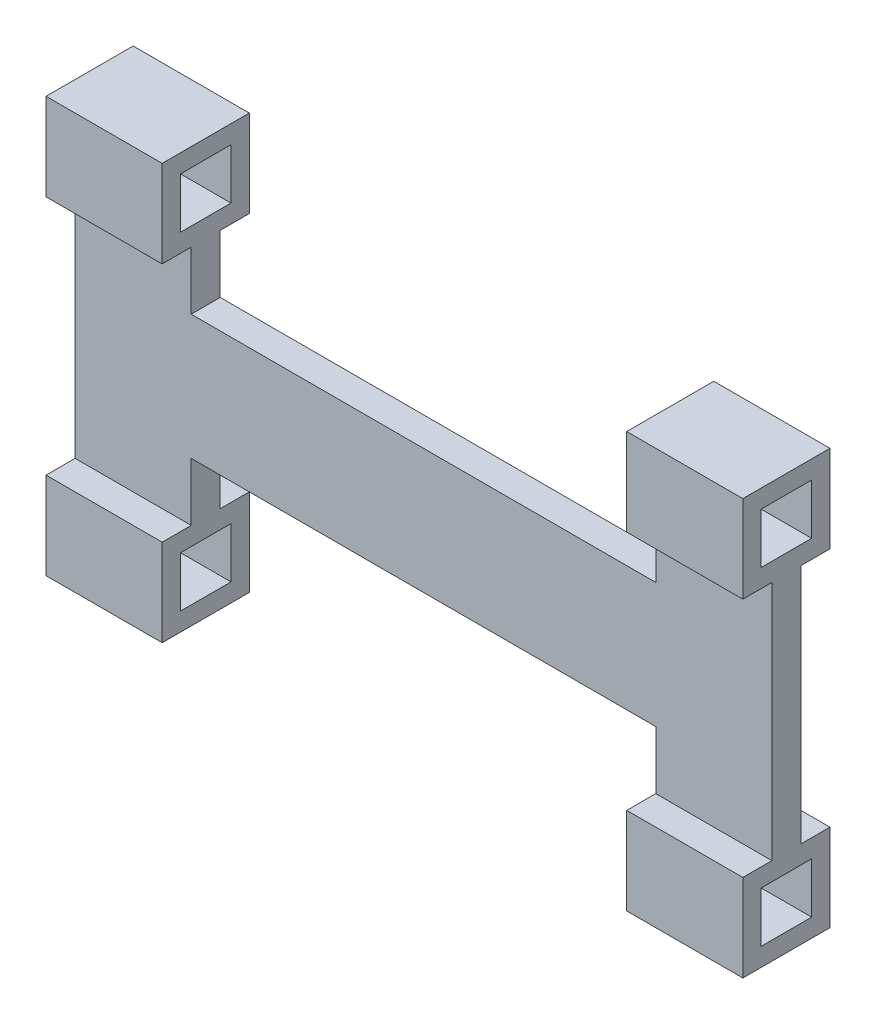
SolidWorks part; units mm, degrees
ref_plane "前视基准面" through (0, 0, 0) normal (0, 0, 1) x (1, 0, 0)
ref_plane "上视基准面" through (0, 0, 0) normal (0, 1, 0) x (1, 0, 0)
ref_plane "右视基准面" through (0, 0, 0) normal (1, 0, 0) x (0, 0, -1)
sketch "草图1" plane through (0, 0, 0) normal (1, 0, 0) x (0, 0, -1)
  line L0 (0, 0) -> (0, 11.3) construction
  line L1 (-0.87, -0.87) -> (0.87, -0.87)
  line L2 (-0.87, -0.87) -> (-0.87, 0.87)
  line L3 (-0.87, 0.87) -> (0.87, 0.87)
  line L4 (0.87, -0.87) -> (0.87, 0.87)
  line L5 (-0.87, -0.87) -> (0.87, 0.87) construction
  line L6 (-0.87, 0.87) -> (0.87, -0.87) construction
  line L7 (-0.87, 10.43) -> (0.87, 10.43)
  line L8 (-0.87, 10.43) -> (-0.87, 12.17)
  line L9 (-0.87, 12.17) -> (0.87, 12.17)
  line L10 (0.87, 10.43) -> (0.87, 12.17)
  line L11 (-0.87, 10.43) -> (0.87, 12.17) construction
  line L12 (-0.87, 12.17) -> (0.87, 10.43) construction
  line L13 (0.5, 9.8) -> (1.5, 9.8)
  line L14 (-1.5, 12.8) -> (1.5, 12.8)
  line L15 (-1.5, 12.8) -> (-1.5, 9.8)
  line L16 (-1.5, 9.8) -> (-0.5, 9.8)
  line L17 (1.5, 12.8) -> (1.5, 9.8)
  line L18 (-1.5, 12.8) -> (1.5, 9.8) construction
  line L19 (-1.5, 9.8) -> (1.5, 12.8) construction
  line L20 (-1.5, 1.5) -> (1.5, 1.5)
  line L21 (-1.5, 1.5) -> (-1.5, -1.5)
  line L22 (-1.5, -1.5) -> (1.5, -1.5)
  line L23 (1.5, 1.5) -> (1.5, -1.5)
  line L24 (-1.5, 1.5) -> (1.5, -1.5) construction
  line L25 (-1.5, -1.5) -> (1.5, 1.5) construction
  line L26 (-0.5, 1.5) -> (0.5, 1.5)
  line L27 (-0.5, 1.5) -> (-0.5, 9.8)
  line L29 (0.5, 1.5) -> (0.5, 9.8)
  line L30 (-0.5, 1.5) -> (0.5, 9.8) construction
  line L31 (-0.5, 9.8) -> (0.5, 1.5) construction
  point P0 (0, 0)
  point P6 (0, 11.3)
  point P21 (0, 5.65)
  dimension "D1" = 11.3
  dimension "D2" = 1.74
  dimension "D3" = 3
  dimension "D4" = 1
extrude "凸台-拉伸1" add sketch "草图1" along normal blind 24 contours L20 L29 L13 L17 L14 L15 L16 L27 L10 L7 L8 L9 | L23 L20 L21 L22 L4 L1 L2 L3
sketch "草图2" plane through (0, 0, 0) normal (0, 0, 1) x (1, 0, 0)
  line L0 (24, 12.8) -> (0, 12.8) construction
  line L1 (4, 17.8) -> (20, 17.8)
  line L2 (4, 17.8) -> (4, 7.8)
  line L3 (4, 7.8) -> (20, 7.8)
  line L4 (20, 17.8) -> (20, 7.8)
  line L5 (4, 17.8) -> (20, 7.8) construction
  line L6 (4, 7.8) -> (20, 17.8) construction
  line L7 (24, -1.5) -> (0, -1.5) construction
  line L8 (4, -6.5) -> (20, -6.5)
  line L9 (4, -6.5) -> (4, 3.5)
  line L10 (4, 3.5) -> (20, 3.5)
  line L11 (20, -6.5) -> (20, 3.5)
  line L12 (4, -6.5) -> (20, 3.5) construction
  line L13 (4, 3.5) -> (20, -6.5) construction
  point P0 (12, 12.8)
  point P7 (12, -1.5)
  dimension "D1" = 16
  dimension "D2" = 10
extrude "切除-拉伸1" cut sketch "草图2" against normal through all both and the other way through all
